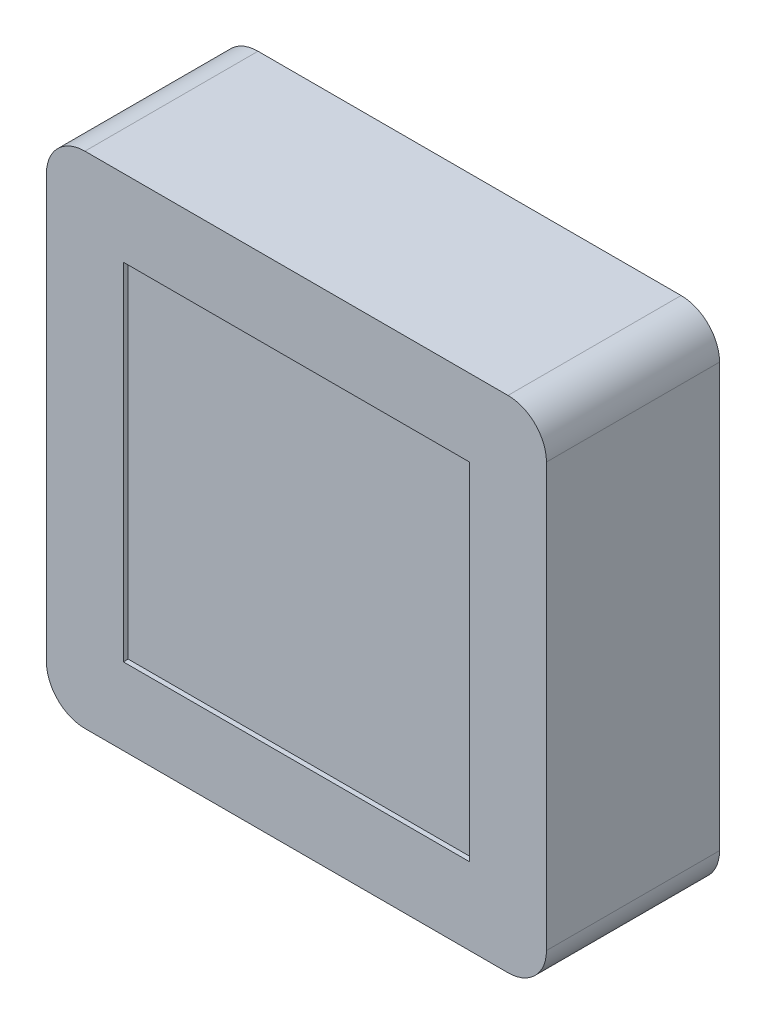
SolidWorks part; units mm, degrees
ref_plane "Front Plane" through (0, 0, 0) normal (0, 0, 1) x (1, 0, 0)
ref_plane "Top Plane" through (0, 0, 0) normal (0, 1, 0) x (1, 0, 0)
ref_plane "Right Plane" through (0, 0, 0) normal (1, 0, 0) x (0, 0, -1)
sketch "Sketch1" plane through (0, 0, 0) normal (0, 0, 1) x (1, 0, 0)
  line L1 (-13, 13) -> (13, 13)
  line L2 (-13, 13) -> (-13, -13)
  line L3 (-13, -13) -> (13, -13)
  line L4 (13, 13) -> (13, -13)
  point P4 (0, 13)
  point P6 (-13, 0)
  dimension "D1" = 26
  dimension "D2" = 26
extrude "Boss-Extrude1" add sketch "Sketch1" along normal mid plane 9
fillet "Fillet1" radius 2 4 edges at (-13, -13, 0) (13, -13, 0) (-13, 13, 0) (13, 13, 0)
sketch "Sketch2" plane through (0, 0, 4.5) normal (0, 0, 1) x (1, 0, 0)
  line L1 (-9, 9) -> (9, 9)
  line L2 (-9, 9) -> (-9, -9)
  line L3 (-9, -9) -> (9, -9)
  line L4 (9, 9) -> (9, -9)
  point P4 (0, 9)
  point P6 (-9, 0)
  dimension "D1" = 18
  dimension "D2" = 18
extrude "Cut-Extrude1" cut sketch "Sketch2" against normal mid plane 0.5
sketch "Sketch3" plane through (0, 0, -4.5) normal (0, 0, -1) x (-1, 0, 0)
  line L0 (0, 4.95) -> (0, -4.95) construction
  circle A0 centre (-9, 0) radius 0.95
  circle A1 centre (9, 0) radius 0.95
  dimension "D1" = 1.9
  dimension "D2" = 9
extrude "Boss-Extrude2" add sketch "Sketch3" along normal mid plane 3
